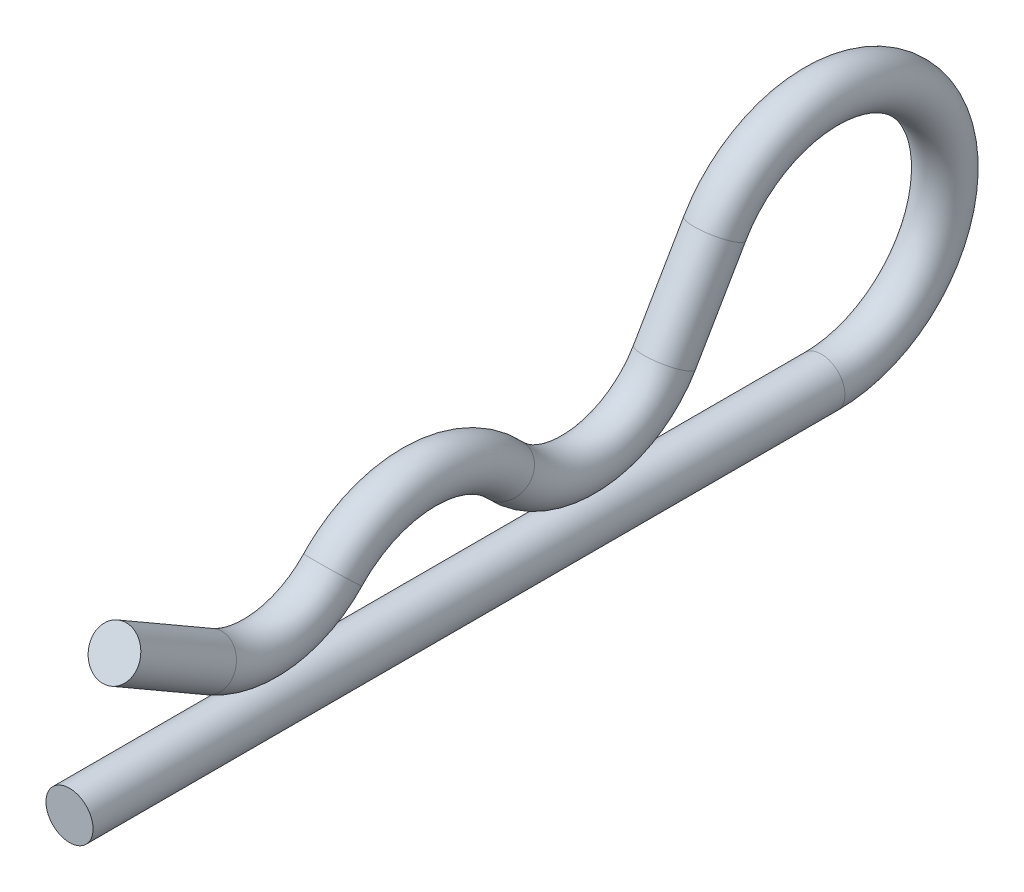
SolidWorks part; units mm, degrees
ref_plane "Front" through (0, 0, 0) normal (0, 0, 1) x (1, 0, 0)
ref_plane "Top" through (0, 0, 0) normal (0, 1, 0) x (1, 0, 0)
ref_plane "Right" through (0, 0, 0) normal (1, 0, 0) x (0, 0, -1)
sketch "Sketch1" plane through (0, 0, 0) normal (1, 0, 0) x (0, 0, -1)
  line L0 (-11.9507, 0) -> (11.9507, 0) construction
  line L1 (-5.894, 0.7493) -> (-5.894, 2.3978) construction
  line L2 (16.6243, 0) -> (16.6243, 3.9243) construction
  line L3 (16.6243, 3.9243) -> (15.875, 3.9243) construction
  line L4 (-11.9507, 0) -> (-11.9507, 0.7493) construction
  line L5 (16.6243, 0) -> (-11.9507, 0) construction
  line L6 (-7.4815, 1.9989) -> (-10.522, 3.7543) construction
  line L7 (-0.8382, 3.7611) -> (-0.8382, 0) construction
  line L8 (-11.9507, 0) -> (-11.9507, -0.7493) construction
  line L13 (8.5583, 5.8971) -> (6.9622, 3.1524) construction
  circle A0 centre (11.9507, 3.9243) radius 3.175 construction
  arc A1 (1.9033, 2.5749) -> (-3.5797, 2.5749) centre (-0.8382, 0) ccw construction
  arc A6 (-3.5797, 2.5749) -> (-7.4815, 1.9989) centre (-5.894, 4.7485) cw construction
  arc A8 (6.9622, 3.1524) -> (1.9033, 2.5749) centre (4.2176, 4.7485) cw construction
  arc A9 (11.9507, 0) -> (8.5583, 5.8971) centre (11.9507, 3.9243) ccw construction
  point P2 (0, 0)
  point P5 (-5.894, 1.5735)
  point P16 (-5.894, 1.5735)
  dimension "D1" = 3.175
  dimension "Eye Diameter" = 6.35
  dimension "D5" = 1.4287
  dimension "D9" = 30
  dimension "D11" = 0.7493
  dimension "D3" = 0.7493
  dimension "Length" = 28.575
  dimension "Wire Diameter" = 1.4986
  dimension "D4" = 3.175
  dimension "D6" = 1.6485
  dimension "D2" = 11.1125
ref_plane "Plane1" through (0, 0, 11.9507) normal (0, 0, 1) x (1, 0, 0)
sketch "Sketch2" plane through (0, 0, 11.9507) normal (0, 0, 1) x (1, 0, 0)
  circle A0 centre (0, 0) radius 0.7493
sketch "Sketch3" plane through (0, 0, 0) normal (1, 0, 0) x (0, 0, -1)
  line L0 (-7.4815, 1.9989) -> (-10.522, 3.7543) construction
  line L1 (8.5583, 5.8971) -> (6.9622, 3.1524) construction
  line L2 (-11.9507, 0) -> (11.9507, 0) construction
  line L3 (-7.4815, 1.9989) -> (-10.522, 3.7543)
  line L4 (8.5583, 5.8971) -> (6.9622, 3.1524)
  line L5 (-11.9507, 0) -> (11.9507, 0)
  arc A0 (-7.4815, 1.9989) -> (-3.5797, 2.5749) centre (-5.894, 4.7485) ccw construction
  arc A1 (1.9033, 2.5749) -> (-3.5797, 2.5749) centre (-0.8382, 0) ccw construction
  arc A2 (1.9033, 2.5749) -> (6.9622, 3.1524) centre (4.2176, 4.7485) ccw construction
  arc A3 (11.9507, 0) -> (8.5583, 5.8971) centre (11.9507, 3.9243) ccw construction
  arc A4 (-7.4815, 1.9989) -> (-3.5797, 2.5749) centre (-5.894, 4.7485) ccw
  arc A5 (1.9033, 2.5749) -> (-3.5797, 2.5749) centre (-0.8382, 0) ccw
  arc A6 (1.9033, 2.5749) -> (6.9622, 3.1524) centre (4.2176, 4.7485) ccw
  arc A7 (11.9507, 0) -> (8.5583, 5.8971) centre (11.9507, 3.9243) ccw
sweep "Sweep1" add profiles "Sketch2" path "Sketch3"
equation "\"D11@Sketch1\" = \"Wire Diameter@Sketch1\" / 2"
equation "\"D1@Sketch1\"=\"Eye Diameter@Sketch1\" / 2"
equation "\"D3@Sketch1\" = \"D11@Sketch1\""
equation "\"D5@Sketch1\" = \"Length@Sketch1\" * .05"
equation "\"D4@Sketch1\"=\"Eye Diameter@Sketch1\"/2"
equation "\"D6@Sketch1\"=\"Wire Diameter@Sketch1\"*1.1"
equation "\"D2@Sketch1\"=( \"Length@Sketch1\" - \"Eye Diameter@Sketch1\" )  / 2"
